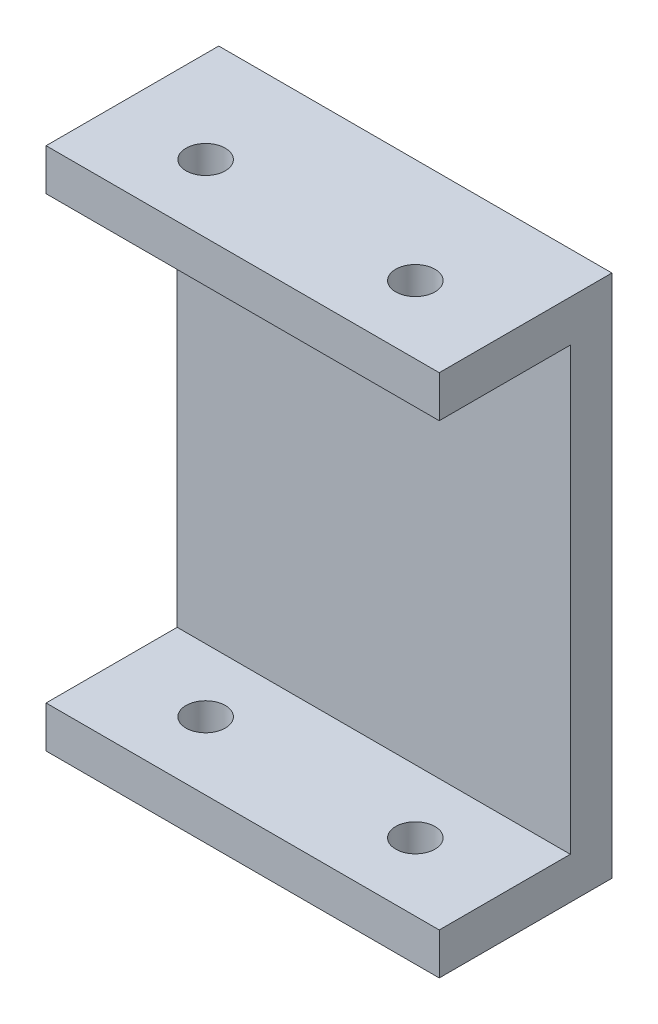
SolidWorks part; units mm, degrees
ref_plane "Front Plane" through (0, 0, 0) normal (0, 0, 1) x (1, 0, 0)
ref_plane "Top Plane" through (0, 0, 0) normal (0, 1, 0) x (1, 0, 0)
ref_plane "Right Plane" through (0, 0, 0) normal (1, 0, 0) x (0, 0, -1)
sketch "Sketch1" plane through (0, 0, 0) normal (0, 0, 1) x (1, 0, 0)
  line L1 (-15, -20) -> (15, -20)
  line L2 (-15, -20) -> (-15, 20)
  line L3 (-15, 20) -> (15, 20)
  line L4 (15, -20) -> (15, 20)
  line L5 (-15, -20) -> (15, 20) construction
  line L6 (-15, 20) -> (15, -20) construction
  point P0 (0, 0)
  dimension "D1" = 30
  dimension "D2" = 40
extrude "Boss-Extrude1" add sketch "Sketch1" along normal blind 3.175
sketch "Sketch3" plane through (0, 0, 3.175) normal (0, 0, 1) x (1, 0, 0)
  line L0 (15, -20) -> (15, 20) construction
  line L1 (-15, 20) -> (15, 20)
  line L2 (-15, 20) -> (-15, 16.825)
  line L3 (-15, 16.825) -> (15, 16.825)
  line L4 (15, 20) -> (15, 16.825)
  line L5 (-15, -20) -> (15, -20) construction
  line L6 (15, -20) -> (-15, -20)
  line L7 (15, -20) -> (15, -16.825)
  line L8 (15, -16.825) -> (-15, -16.825)
  line L9 (-15, -20) -> (-15, -16.825)
  line L10 (-15, 20) -> (-15, -20) construction
  dimension "D1" = 3.175
  dimension "D2" = 3.175
extrude "Boss-Extrude2" add sketch "Sketch3" along normal blind 10
sketch "Sketch4" plane through (0, 20, 0) normal (0, 1, 0) x (1, 0, 0)
  line L0 (-8, -8) -> (8, -8) construction
  line L1 (0, -7.2462) -> (0, 7.2462) construction
  line L3 (-16.5, 0) -> (16.5, 0) construction
  circle A0 centre (-8, -8) radius 1.5
  circle A1 centre (8, -8) radius 1.5
  point P4 (0, -8)
  point P7 (0, 0)
  point P10 (0, 0)
  dimension "D1" = 3
  dimension "D2" = 8
  dimension "D3" = 8
extrude "Cut-Extrude1" cut sketch "Sketch4" against normal through all both and the other way through all
